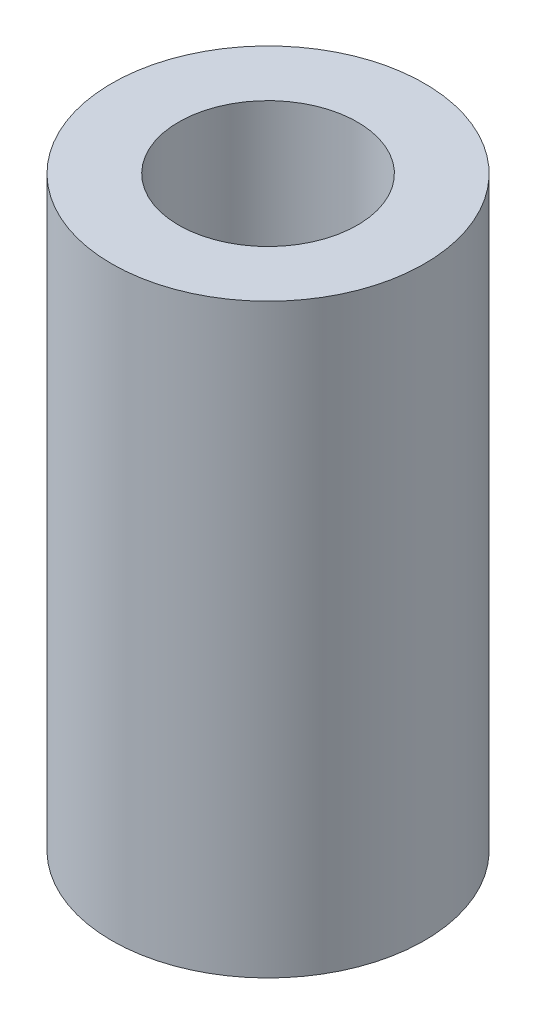
SolidWorks part; units mm, degrees
ref_plane "Front" through (0, 0, 0) normal (0, 0, 1) x (1, 0, 0)
ref_plane "Top" through (0, 0, 0) normal (0, 1, 0) x (1, 0, 0)
ref_plane "Right" through (0, 0, 0) normal (1, 0, 0) x (0, 0, -1)
sketch "Sketch2" plane through (0, 0, 0) normal (0, 1, 0) x (1, 0, 0)
  circle A0 centre (0, 0) radius 5.335
  circle A1 centre (0, 0) radius 3.05
  dimension "D1" = 10.67
  dimension "D2" = 6.1
extrude "Boss-Extrude1" add sketch "Sketch2" along normal blind 20
